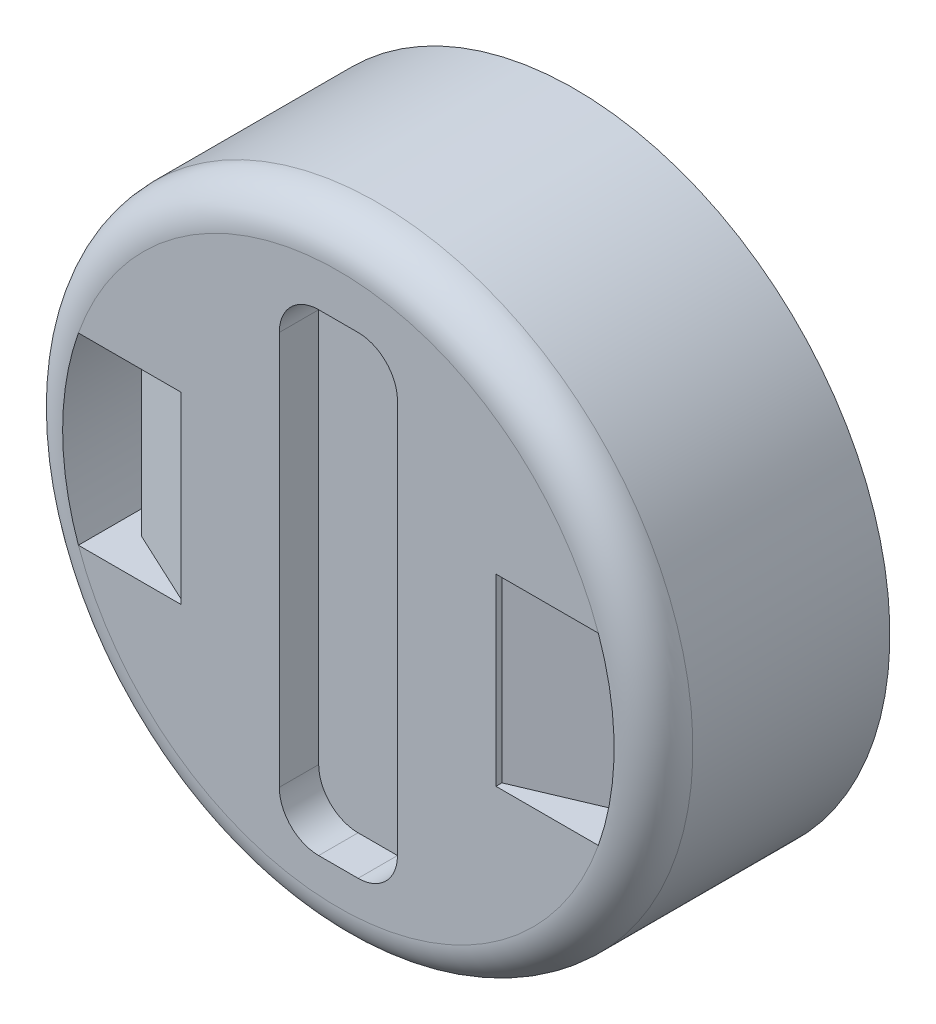
SolidWorks part; units mm, degrees
material "AISI 304"
ref_plane "Front Plane" through (0, 0, 0) normal (0, 0, 1) x (1, 0, 0)
ref_plane "Top Plane" through (0, 0, 0) normal (0, 1, 0) x (1, 0, 0)
ref_plane "Right Plane" through (0, 0, 0) normal (1, 0, 0) x (0, 0, -1)
sketch "草图1" plane through (0, 0, 12) normal (0, 0, -1) x (-1, 0, 0)
  circle A0 centre (0, 0) radius 8
extrude "凸台-拉伸1" add sketch "草图1" against normal blind 6
fillet "圆角1" radius 1 1 edges at (-8, 0, 18)
sketch "草图3" plane through (0, 0, 18) normal (0, 0, 1) x (1, 0, 0)
  line L0 (0, 8) -> (0, -8) construction
  line L1 (-1.5, 5.8946) -> (1.5, 5.8946)
  line L2 (-1.5, 5.8946) -> (-1.5, -6.1054)
  line L3 (-1.5, -6.1054) -> (1.5, -6.1054)
  line L4 (1.5, 5.8946) -> (1.5, -6.1054)
  point P5 (0, 5.8946)
extrude "切除-拉伸1" cut sketch "草图3" against normal blind 1
fillet "圆角2" radius 1 4 edges at (1.5, -6.1054, 17.5) (-1.5, -6.1054, 17.5) (1.5, 5.8946, 17.5) (-1.5, 5.8946, 17.5)
sketch "草图4" plane through (0, 0, 18) normal (0, 0, 1) x (1, 0, 0)
  line L1 (-6.5997, 2.3333) -> (-4, 2.3333)
  line L2 (-6.5997, -2.3333) -> (-4, -2.3333)
  line L3 (4, -2.3333) -> (6.5997, -2.3333)
  line L5 (4, 2.3333) -> (6.5997, 2.3333)
  line L6 (-4, 2.3333) -> (-4, -2.3333)
  line L8 (4, 2.3333) -> (4, -2.3333)
  arc A1 (-6.5997, 2.3333) -> (-6.5997, -2.3333) centre (0, 0) ccw
  arc A4 (6.5997, -2.3333) -> (6.5997, 2.3333) centre (0, 0) ccw
extrude "切除-拉伸2" cut sketch "草图4" against normal blind 1
chamfer "倒角2" distance 2 angle 25 1 edges at (-4, 0, 17)
chamfer "倒角5" distance 2 angle 23 1 edges at (4, 0, 17)
sketch "草图6" plane through (0, 0, 17) normal (0, 0, 1) x (1, 0, 0)
  line L0 (-6.5997, -2.3333) -> (-6, -2.3333) construction
  line L1 (-6, -2.3333) -> (-6, 2.3333) construction
  line L2 (-6, 2.3333) -> (-6.5997, 2.3333) construction
  line L3 (6.5997, 2.3333) -> (6, 2.3333) construction
  line L4 (6, 2.3333) -> (6, -2.3333) construction
  line L5 (6, -2.3333) -> (6.5997, -2.3333) construction
  line L6 (-6.5997, -2.3333) -> (-6, -2.3333)
  line L7 (-6, -2.3333) -> (-6, 2.3333)
  line L8 (-6, 2.3333) -> (-6.5997, 2.3333)
  line L9 (6.5997, 2.3333) -> (6, 2.3333)
  line L10 (6, 2.3333) -> (6, -2.3333)
  line L11 (6, -2.3333) -> (6.5997, -2.3333)
  arc A0 (-6.5997, 2.3333) -> (-6.5997, -2.3333) centre (0, 0) ccw construction
  arc A1 (6.5997, -2.3333) -> (6.5997, 2.3333) centre (0, 0) ccw construction
  arc A2 (-6.5997, 2.3333) -> (-6.5997, -2.3333) centre (0, 0) ccw
  arc A3 (6.5997, -2.3333) -> (6.5997, 2.3333) centre (0, 0) ccw
extrude "切除-拉伸3" cut sketch "草图6" against normal blind 8
sketch "草图7" plane through (0, 0, 12) normal (0, 0, -1) x (-1, 0, 0)
  circle A0 centre (0, 0) radius 7
extrude "切除-拉伸4" cut sketch "草图7" against normal blind 4
